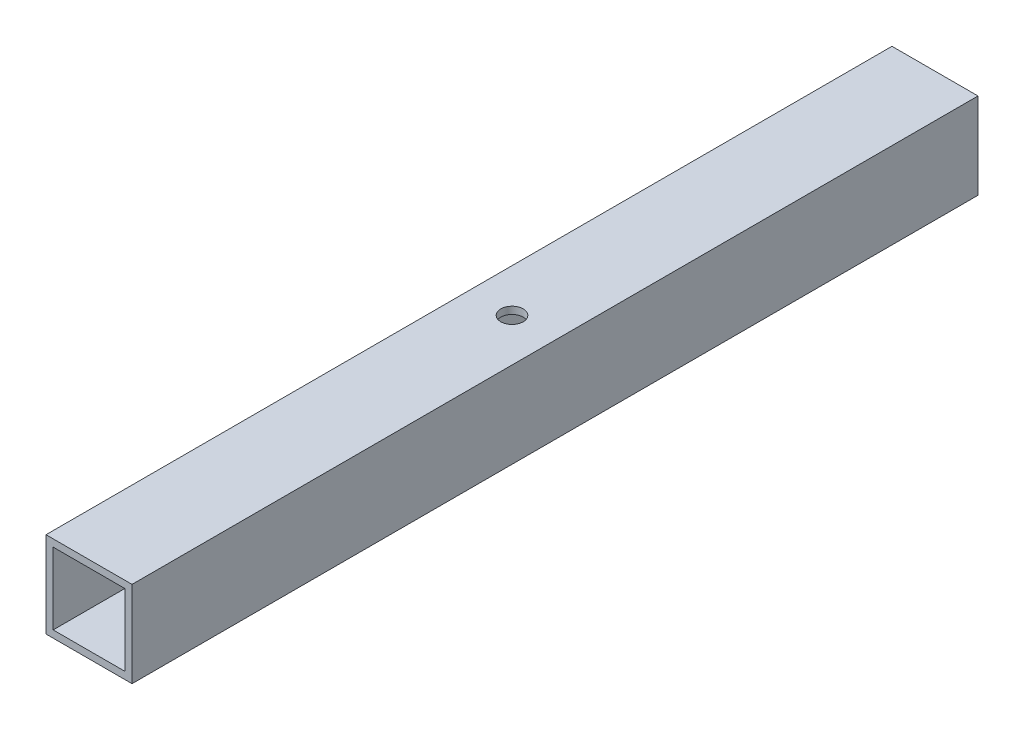
SolidWorks part; units mm, degrees
material "6061 Alloy"
ref_plane "Front Plane" through (0, 0, 0) normal (0, 0, 1) x (1, 0, 0)
ref_plane "Top Plane" through (0, 0, 0) normal (0, 1, 0) x (1, 0, 0)
ref_plane "Right Plane" through (0, 0, 0) normal (1, 0, 0) x (0, 0, -1)
sketch "Sketch1" plane through (0, 0, 0) normal (0, 0, 1) x (1, 0, 0)
  line L0 (-15.875, 15.875) -> (15.875, 15.875)
  line L1 (-19.05, -19.05) -> (19.05, -19.05)
  line L2 (-19.05, -19.05) -> (-19.05, 19.05)
  line L3 (-19.05, 19.05) -> (19.05, 19.05)
  line L4 (19.05, -19.05) -> (19.05, 19.05)
  line L5 (-19.05, -19.05) -> (19.05, 19.05) construction
  line L6 (-19.05, 19.05) -> (19.05, -19.05) construction
  line L7 (15.875, -15.875) -> (15.875, 15.875)
  line L8 (-15.875, -15.875) -> (15.875, -15.875)
  line L9 (-15.875, -15.875) -> (-15.875, 15.875)
  point P0 (0, 0)
  dimension "D1" = 38.1
  dimension "D2" = 3.175
extrude "Boss-Extrude1" add sketch "Sketch1" along normal blind 374.65
hole_wizard "25/64 (0.39063) Diameter Hole1" positions "Sketch2" profile "Sketch3" hole size "25/64" standard "ANSI Inch" end condition through all
sketch "Sketch2" plane through (0, 19.05, 0) normal (0, 1, 0) x (1, 0, 0)
  line L0 (19.05, -187.325) -> (-19.05, -187.325) construction
  line L1 (19.05, -374.65) -> (19.05, 0) construction
  line L2 (-19.05, -374.65) -> (-19.05, 0) construction
  point P0 (0, -187.325)
sketch "Sketch3" plane through (0, 19.05, 187.325) normal (1, 0, 0) x (0, 0, 1)
  line L0 (0, 0) -> (0, 38.1)
  line L1 (0, 38.1) -> (4.961, 38.1)
  line L2 (4.961, 38.1) -> (4.961, 0)
  line L5 (4.961, 0) -> (0, 0)
  line L11 (0, -6.35) -> (0, 107.95) construction
  dimension "Thru Hole Dia." = 9.922
  dimension "Thru Hole Depth" = 38.1
